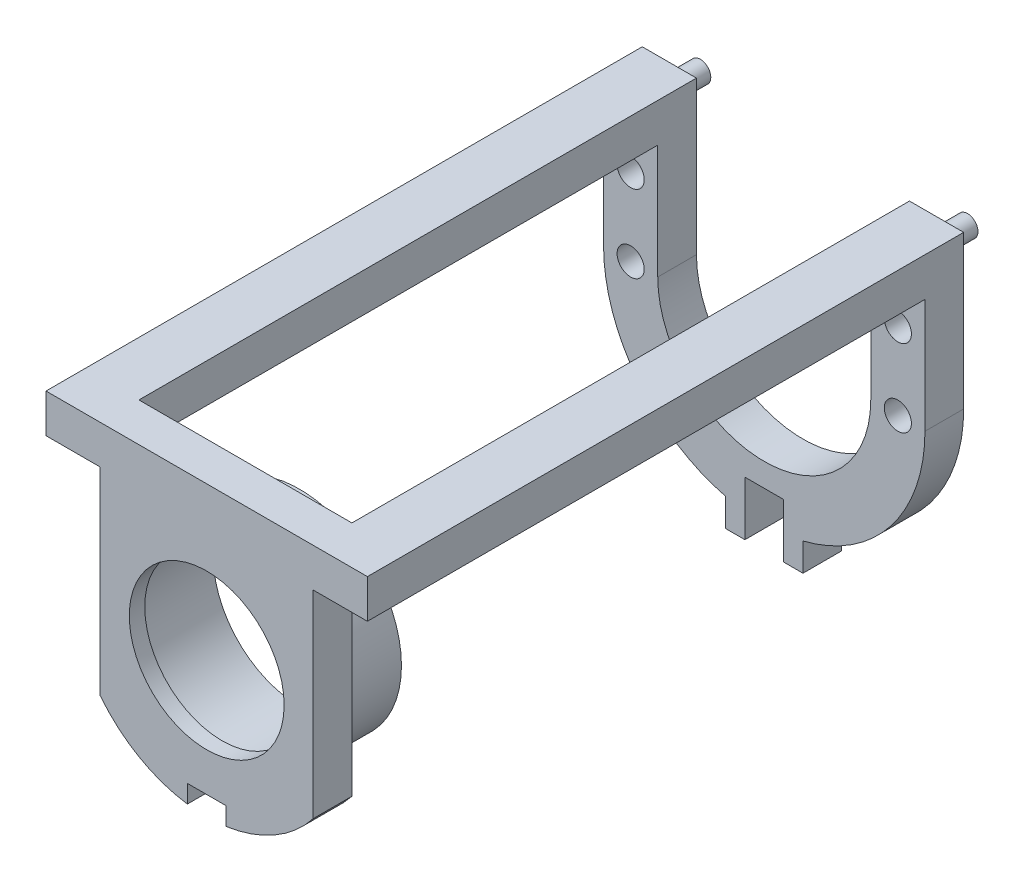
SolidWorks part; units mm, degrees
ref_plane "Front Plane" through (0, 0, 0) normal (0, 0, 1) x (1, 0, 0)
ref_plane "Top Plane" through (0, 0, 0) normal (0, 1, 0) x (1, 0, 0)
ref_plane "Right Plane" through (0, 0, 0) normal (1, 0, 0) x (0, 0, -1)
sketch "Sketch1" plane through (0, 0, 0) normal (0, 0, 1) x (1, 0, 0)
  line L13 (-13.7532, 0) -> (-13.7532, 19.75)
  line L14 (-13.7532, 19.75) -> (-20.7532, 19.75)
  line L15 (-20.7532, 19.75) -> (-20.7532, 0)
  line L16 (-5, -20.1419) -> (-5, -23.7532)
  line L17 (-5, -23.7532) -> (-2.5, -23.7532)
  line L18 (-2.5, -23.7532) -> (-2.5, -16.7532)
  line L19 (-2.5, -16.7532) -> (2.5, -16.7532)
  line L20 (2.5, -16.7532) -> (2.5, -23.7532)
  line L21 (2.5, -23.7532) -> (5, -23.7532)
  line L22 (5, -23.7532) -> (5, -20.1419)
  line L23 (20.7532, 0) -> (20.7532, 19.75)
  line L24 (20.7532, 19.75) -> (13.7532, 19.75)
  line L25 (13.7532, 19.75) -> (13.7532, 0)
  line L26 (-13.7532, 0) -> (-13.7532, 19.75)
  line L27 (-13.7532, 19.75) -> (-20.7532, 19.75)
  line L28 (-20.7532, 19.75) -> (-20.7532, 0)
  line L29 (-5, -20.1419) -> (-5, -23.7532)
  line L30 (-5, -23.7532) -> (-2.5, -23.7532)
  line L31 (-2.5, -23.7532) -> (-2.5, -16.7532)
  line L32 (-2.5, -16.7532) -> (2.5, -16.7532)
  line L33 (2.5, -16.7532) -> (2.5, -23.7532)
  line L34 (2.5, -23.7532) -> (5, -23.7532)
  line L35 (5, -23.7532) -> (5, -20.1419)
  line L36 (20.7532, 0) -> (20.7532, 19.75)
  line L37 (20.7532, 19.75) -> (13.7532, 19.75)
  line L38 (13.7532, 19.75) -> (13.7532, 0)
  circle A0 centre (-17.2532, 0) radius 1.75 construction
  circle A1 centre (-17.2532, 10) radius 1.75 construction
  circle A2 centre (17.2532, 10) radius 1.75 construction
  arc A3 (-20.7532, 0) -> (-5, -20.1419) centre (0, 0) ccw
  arc A4 (5, -20.1419) -> (20.7532, 0) centre (0, 0) ccw
  arc A5 (-13.7532, 0) -> (13.7532, 0) centre (0, 0) ccw
  arc A6 (-20.7532, 0) -> (-5, -20.1419) centre (0, 0) ccw
  arc A7 (5, -20.1419) -> (20.7532, 0) centre (0, 0) ccw
  arc A8 (-13.7532, 0) -> (13.7532, 0) centre (0, 0) ccw
  circle A9 centre (17.2532, 0) radius 1.75 construction
  circle A10 centre (-17.2532, 0) radius 1.75
  circle A11 centre (-17.2532, 10) radius 1.75
  circle A12 centre (17.2532, 10) radius 1.75
  circle A13 centre (17.2532, 0) radius 1.75
  dimension "D1" = 0
extrude "Boss-Extrude1" add sketch "Sketch1" along normal blind 5
sketch "Sketch2" plane through (0, 0, 0) normal (0, 0, -1) x (-1, 0, 0)
  circle A0 centre (-17.2532, 16.75) radius 1.35 construction
  circle A1 centre (-17.2532, 16.75) radius 1.35
  circle A3 centre (17.2532, 16.75) radius 1.35
  circle A4 centre (17.2532, 16.75) radius 1.35
  dimension "D1" = 0
extrude "Boss-Extrude2" add sketch "Sketch2" along normal blind 4
sketch "Sketch4" plane through (0, 0, 5) normal (0, 0, 1) x (1, 0, 0)
  line L0 (-13.7532, 0) -> (-13.7532, 19.75) construction
  line L1 (-20.7532, 19.75) -> (-13.7532, 19.75)
  line L2 (-20.7532, 19.75) -> (-20.7532, 14.75)
  line L3 (-20.7532, 14.75) -> (-13.7532, 14.75)
  line L4 (-13.7532, 19.75) -> (-13.7532, 14.75)
  line L5 (20.7532, 0) -> (20.7532, 19.75) construction
  line L6 (13.7532, 19.75) -> (20.7532, 19.75)
  line L7 (13.7532, 19.75) -> (13.7532, 14.75)
  line L8 (13.7532, 14.75) -> (20.7532, 14.75)
  line L9 (20.7532, 19.75) -> (20.7532, 14.75)
  dimension "D1" = 5
  dimension "D2" = 5
extrude "Boss-Extrude3" add sketch "Sketch4" along normal up to surface (72 mm away)
sketch "Sketch5" plane through (0, 0, 77) normal (0, 0, 1) x (1, 0, 0)
  line L0 (-13.7532, 14.75) -> (-13.7532, -10.8213)
  line L1 (13.7532, 14.75) -> (13.7532, -10.8213)
  line L2 (-13.7532, 19.75) -> (13.7532, 19.75)
  line L3 (-13.7532, 19.75) -> (-13.7532, -10.8213)
  line L4 (13.7532, -10.8213) -> (13.7532, 19.75)
  circle A0 centre (0, 0) radius 10
  arc A1 (-13.7532, -10.8213) -> (13.7532, -10.8213) centre (0, 0) ccw
  dimension "D1" = 20
  dimension "D2" = 35
extrude "Boss-Extrude4" add sketch "Sketch5" against normal blind 5 contours L0 A1 L1 L4 L2 L3 A0
sketch "Sketch6" plane through (0, 0, 72) normal (0, 0, -1) x (-1, 0, 0)
  circle A0 centre (0, 0) radius 11.15
  circle A1 centre (0, 0) radius 13.15
  dimension "D1" = 22.3
  dimension "D2" = 2
extrude "Boss-Extrude5" add sketch "Sketch6" along normal blind 7
sketch "Sketch7" plane through (0, 0, 72) normal (0, 0, -1) x (-1, 0, 0)
  circle A1 centre (0, 0) radius 11.15
  circle A2 centre (0, 0) radius 11.15
  dimension "D1" = 0
extrude "Cut-Extrude1" cut sketch "Sketch7" against normal blind 3
sketch "Sketch8" plane through (0, 0, 77) normal (0, 0, 1) x (1, 0, 0)
  line L1 (2.5, -17.3205) -> (2.5, -15)
  line L2 (-2.5, -17.3205) -> (-2.5, -15)
  line L3 (-2.5, -15) -> (2.5, -15)
  arc A0 (-13.7532, -10.8213) -> (13.7532, -10.8213) centre (0, 0) ccw construction
  arc A1 (-2.5, -17.3205) -> (2.5, -17.3205) centre (0, 0) ccw
extrude "Cut-Extrude2" cut sketch "Sketch8" against normal blind 5
